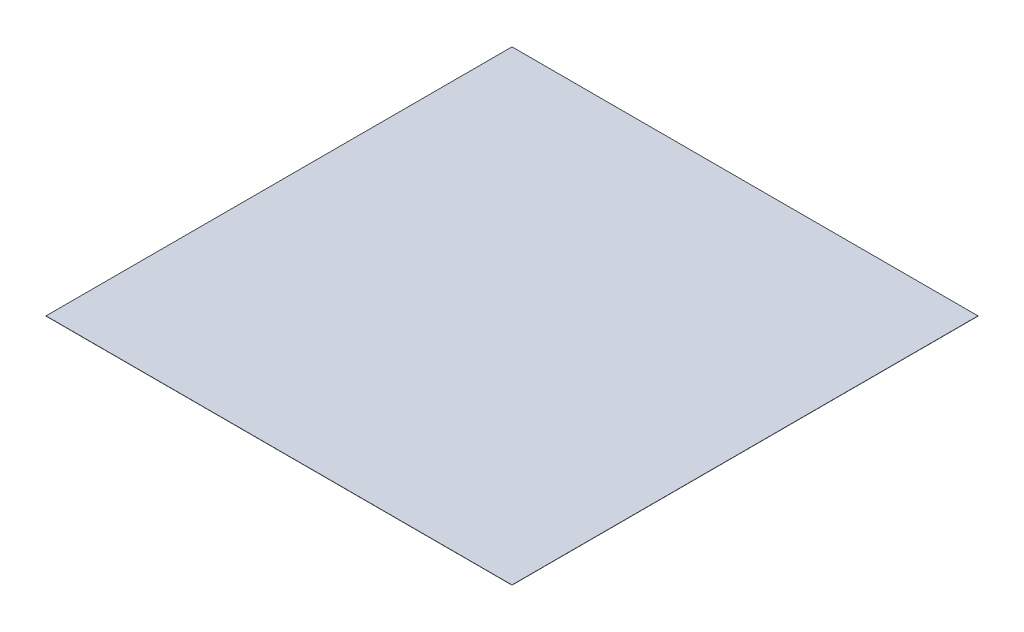
SolidWorks part; units mm, degrees
ref_plane "前视基准面" through (0, 0, 0) normal (0, 0, 1) x (1, 0, 0)
ref_plane "上视基准面" through (0, 0, 0) normal (0, 1, 0) x (1, 0, 0)
ref_plane "右视基准面" through (0, 0, 0) normal (1, 0, 0) x (0, 0, -1)
sketch "草图1" plane through (0, 0, 0) normal (0, 1, 0) x (1, 0, 0)
  line L1 (-1200, 1200) -> (1200, 1200)
  line L2 (-1200, 1200) -> (-1200, -1200)
  line L3 (-1200, -1200) -> (1200, -1200)
  line L4 (1200, 1200) -> (1200, -1200)
  line L5 (-1200, 1200) -> (1200, -1200) construction
  line L6 (-1200, -1200) -> (1200, 1200) construction
  point P0 (0, 0)
  dimension "D1" = 2400
  dimension "D2" = 2400
extrude "凸台-拉伸1" add sketch "草图1" along normal blind 1
ref_plane "基准面1" through (0, 1, 0) normal (0, 1, 0) x (1, 0, 0)
sketch "草图2" plane through (0, 1, 0) normal (0, 1, 0) x (1, 0, 0)
  line L0 (1200, 1200) -> (-1200, 1200) construction
  line L1 (1200, 1200) -> (900, 1200) construction
  line L2 (1200, 1200) -> (1200, 900) construction
  line L3 (1200, 900) -> (900, 900) construction
  line L4 (900, 1200) -> (900, 900) construction
  line L5 (-1050, -1050) -> (1050, -1050) construction
  line L6 (-1050, -1050) -> (-1050, 1120) construction
  line L7 (-1050, 1120) -> (1050, 1120) construction
  line L8 (1050, -1050) -> (1050, 1120) construction
  line L9 (-1200, -1200) -> (1200, -1200) construction
  line L10 (-1200, 1200) -> (-1200, -1200) construction
  line L11 (1200, -1200) -> (1200, 1200) construction
  line L12 (-1200, 0) -> (1200, 0) construction
  line L13 (-1125, 150) -> (-1125, -150) construction
  line L14 (-1050, 290) -> (-1200, 290) construction
  line L15 (-1050, 290) -> (-1050, -290) construction
  line L16 (-1050, -290) -> (-1200, -290) construction
  line L17 (-1200, 290) -> (-1200, -290) construction
  line L18 (-1050, 290) -> (-1200, -290) construction
  line L19 (-1050, -290) -> (-1200, 290) construction
  line L20 (0, 1200) -> (0, -1200) construction
  line L21 (-150, -1125) -> (0, -1125) construction
  line L22 (-290, -1050) -> (290, -1050) construction
  line L23 (-290, -1050) -> (-290, -1200) construction
  line L24 (-290, -1200) -> (290, -1200) construction
  line L25 (290, -1050) -> (290, -1200) construction
  line L26 (-290, -1050) -> (290, -1200) construction
  line L27 (-290, -1200) -> (290, -1050) construction
  line L28 (0, -1125) -> (150, -1125) construction
  line L30 (200, 670) -> (600, 670) construction
  line L31 (200, 670) -> (200, 235) construction
  line L32 (200, 235) -> (600, 235) construction
  line L33 (600, 670) -> (600, 235) construction
  line L34 (200, 670) -> (600, 235) construction
  line L35 (200, 235) -> (600, 670) construction
  line L36 (200, -165) -> (600, -165) construction
  line L37 (200, -165) -> (200, -600) construction
  line L38 (200, -600) -> (600, -600) construction
  line L39 (600, -165) -> (600, -600) construction
  line L40 (200, -165) -> (600, -600) construction
  line L41 (200, -600) -> (600, -165) construction
  line L42 (-600, 670) -> (-200, 670) construction
  line L43 (-600, 670) -> (-600, 235) construction
  line L44 (-600, 235) -> (-200, 235) construction
  line L45 (-200, 670) -> (-200, 235) construction
  line L46 (-600, 670) -> (-200, 235) construction
  line L47 (-600, 235) -> (-200, 670) construction
  line L48 (-600, -165) -> (-200, -165) construction
  line L49 (-600, -165) -> (-600, -600) construction
  line L50 (-600, -600) -> (-200, -600) construction
  line L51 (-200, -165) -> (-200, -600) construction
  line L52 (-600, -165) -> (-200, -600) construction
  line L53 (-600, -600) -> (-200, -165) construction
  circle A0 centre (-1125, 0) radius 25 construction
  circle A1 centre (-1125, 150) radius 25 construction
  circle A2 centre (-1125, -150) radius 25 construction
  circle A3 centre (0, -1125) radius 25 construction
  circle A4 centre (150, -1125) radius 25 construction
  circle A5 centre (-150, -1125) radius 25 construction
  circle A6 centre (-400, 1270) radius 150 construction
  circle A7 centre (-400, 1270) radius 120 construction
  circle A8 centre (-400, 1390) radius 25 construction
  circle A9 centre (-296.077, 1330) radius 25 construction
  circle A10 centre (-296.077, 1210) radius 25 construction
  circle A11 centre (-400, 1150) radius 25 construction
  circle A12 centre (-503.923, 1210) radius 25 construction
  circle A13 centre (-503.923, 1330) radius 25 construction
  point P19 (-1125, 0)
  point P30 (0, -1125)
  point P43 (400, 452.5)
  point P48 (400, -382.5)
  point P53 (-400, 452.5)
  point P58 (-400, -382.5)
  point P81 (-400, 1270)
  dimension "D10" = 50
  dimension "D11" = 50
  dimension "D12" = 50
  dimension "D14" = 50
  dimension "D15" = 50
  dimension "D16" = 50
  dimension "D29" = 300
  dimension "D31" = 50
  dimension "D32" = 120
  dimension "D1" = 300
  dimension "D2" = 300
  dimension "D3" = 80
  dimension "D4" = 150
  dimension "D5" = 150
  dimension "D6" = 150
  dimension "D7" = 580
  dimension "D8" = 150
  dimension "D9" = 150
  dimension "D13" = 580
  dimension "D17" = 150
  dimension "D18" = 150
  dimension "D19" = 450
  dimension "D20" = 400
  dimension "D21" = 400
  dimension "D22" = 400
  dimension "D23" = 400
  dimension "D24" = 450
  dimension "D25" = 450
  dimension "D26" = 450
  dimension "D27" = 400
  dimension "D28" = 435
  dimension "D30" = 650
  dimension "D33" = 6
